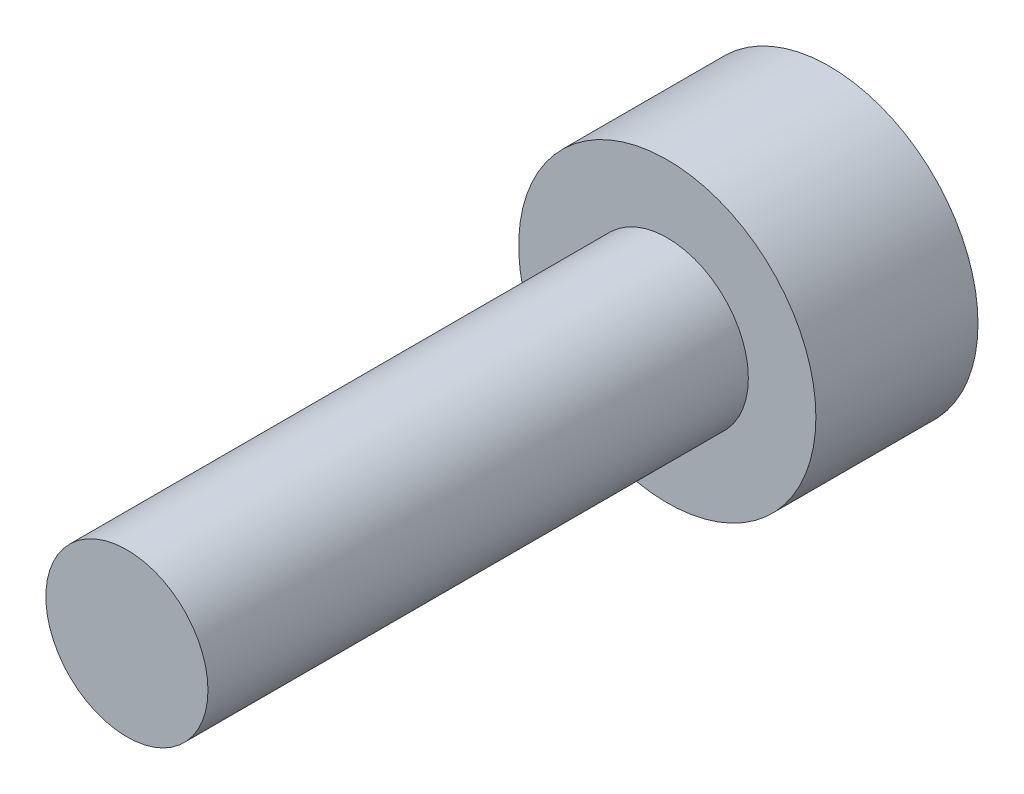
SolidWorks part; units mm, degrees
material "AISI 304"
ref_plane "Alzado" through (0, 0, 0) normal (0, 0, 1) x (1, 0, 0)
ref_plane "Planta" through (0, 0, 0) normal (0, 1, 0) x (1, 0, 0)
ref_plane "Vista lateral" through (0, 0, 0) normal (1, 0, 0) x (0, 0, -1)
sketch "Sk_Cabeza" plane through (0, 0, 0) normal (0, 0, 1) x (1, 0, 0)
  circle A0 centre (0, 0) radius 2.75
  dimension "D1" = 5.5
extrude "Cabeza" add sketch "Sk_Cabeza" along normal blind 3 from offset 3
sketch "Sk_Cuerpo" plane through (0, 0, 0) normal (0, 0, 1) x (1, 0, 0)
  circle A0 centre (0, 0) radius 1.5
  dimension "D1" = 3
extrude "Cuerpo" add sketch "Sk_Cuerpo" along normal blind 10
sketch "Sk_Hexagono_interior" plane through (0, 0, 0) normal (0, 0, 1) x (1, 0, 0)
  line L1 (0, -1.4434) -> (1.25, -0.7217)
  line L2 (1.25, -0.7217) -> (1.25, 0.7217)
  line L3 (1.25, 0.7217) -> (0, 1.4434)
  line L4 (0, 1.4434) -> (-1.25, 0.7217)
  line L5 (-1.25, 0.7217) -> (-1.25, -0.7217)
  line L6 (-1.25, -0.7217) -> (0, -1.4434)
  circle A0 centre (0, 0) radius 1.25 construction
  dimension "D1" = 2.5
extrude "Hexagono_interior" cut sketch "Sk_Hexagono_interior" along normal blind 1.5 from offset 3
